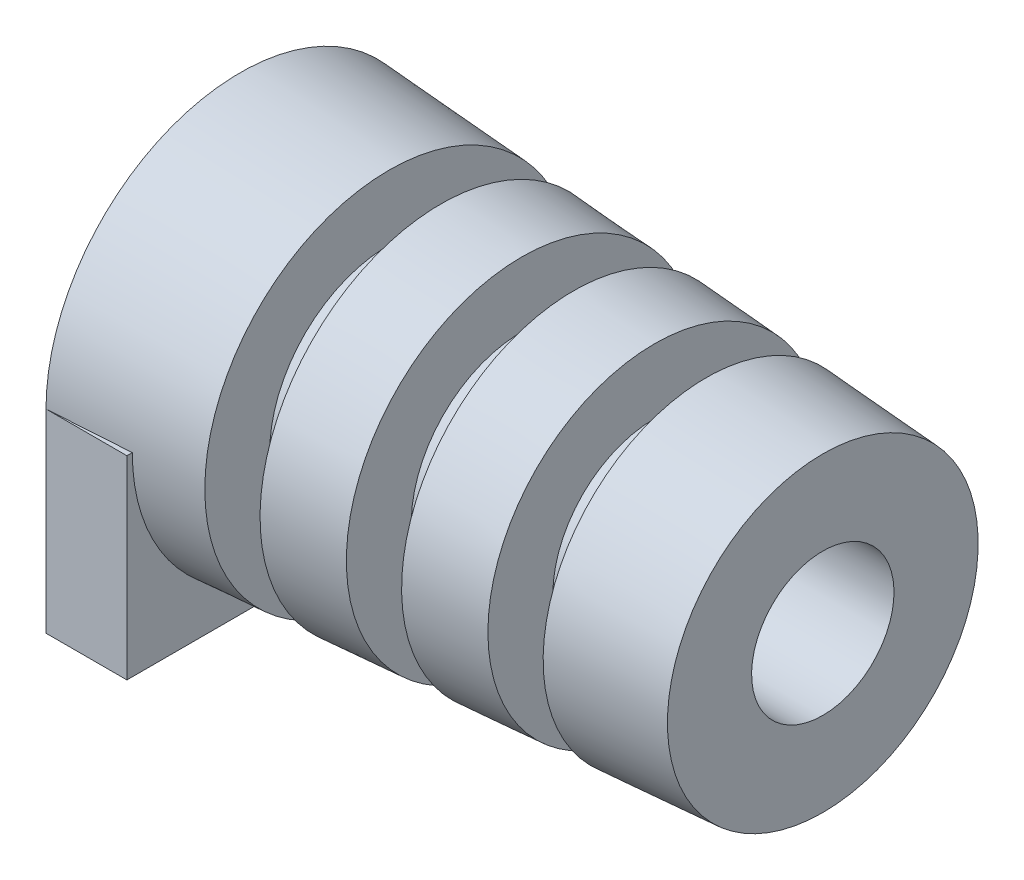
SolidWorks part; units mm, degrees
material "Rubber"
ref_plane "Front" through (0, 0, 0) normal (0, 0, 1) x (1, 0, 0)
ref_plane "Top" through (0, 0, 0) normal (0, 1, 0) x (1, 0, 0)
ref_plane "Right" through (0, 0, 0) normal (1, 0, 0) x (0, 0, -1)
sketch "Sketch2" plane through (54.9, 0, 50.4016) normal (0, 0, -1) x (-1, 0, 0)
  line L0 (54.6382, 2.5902) -> (31.7782, 2.5902)
  line L1 (36.3502, -1.0166) -> (36.3502, 1.5291)
  line L2 (36.3502, -2.2358) -> (36.3502, 2.5902) construction
  line L3 (54.6382, -2.2358) -> (54.6382, 2.5902)
  line L4 (54.6382, 5.3842) -> (31.7782, 5.3842) construction
  line L5 (31.7782, 2.5902) -> (31.7782, -0.7118)
  line L6 (31.7782, -0.7118) -> (36.3502, -1.0166)
  line L7 (48.7962, -1.8463) -> (48.7962, 0.6993)
  line L8 (46.7642, -1.7108) -> (46.7642, 0.8348)
  line L9 (43.5892, -1.4992) -> (43.5892, 1.0465)
  line L10 (41.5572, -1.3637) -> (41.5572, 1.1819)
  line L11 (38.3822, -1.152) -> (38.3822, 1.3936)
  line L12 (36.3502, 1.5291) -> (38.3822, 1.3936)
  line L13 (48.7962, -1.8463) -> (54.6382, -2.2358)
  line L14 (31.7782, -0.7118) -> (54.6382, -2.2358) construction
  line L15 (48.7962, -2.2358) -> (48.7962, 2.5902) construction
  line L16 (46.7642, -2.2358) -> (46.7642, 2.5902) construction
  line L17 (54.6382, 0.3099) -> (54.8072, 0.2986)
  line L18 (31.9472, 1.8226) -> (54.8072, 0.2986) construction
  line L19 (46.7642, 0.8348) -> (48.7962, 0.6993)
  line L20 (43.5892, -2.2358) -> (43.5892, 2.5902) construction
  line L21 (41.5572, -2.2358) -> (41.5572, 2.5902) construction
  line L22 (38.3822, -2.2358) -> (38.3822, 2.5902) construction
  line L23 (41.5572, 1.1819) -> (43.5892, 1.0465)
  line L24 (38.3822, -1.152) -> (41.5572, -1.3637)
  line L25 (43.5892, -1.4992) -> (46.7642, -1.7108)
  dimension "D1" = 7.62
  dimension "D2" = 22.86
  dimension "D3" = 6.096
  dimension "D4" = 2.794
  dimension "D5" = 5.842
  dimension "D6" = 2.032
  dimension "D7" = 3.175
  dimension "D8" = 2.032
  dimension "D9" = 3.175
  dimension "D10" = 2.54
  dimension "D11" = 2.032
revolve "Revolve-Thin2" add sketch "Sketch2" angle 360 about L4
sketch "Sketch4" plane through (0.2616, 0, 0) normal (-1, 0, 0) x (0, 0, 1)
  line L0 (42.7814, 5.3842) -> (58.0219, 5.3842) construction
  line L1 (42.7814, 5.3842) -> (42.7814, -2.236)
  line L2 (50.4016, -2.236) -> (50.4016, 13.0045) construction
  line L3 (42.7814, -2.236) -> (58.0219, -2.236)
  line L4 (57.5136, 5.3842) -> (58.0219, 5.3842)
  line L5 (43.2896, 5.3842) -> (42.7814, 5.3842)
  line L6 (58.0219, 5.3842) -> (58.0219, -2.236)
  circle A0 centre (50.4016, 5.3842) radius 7.6202 construction
  arc A1 (43.2896, 5.3842) -> (57.5136, 5.3842) centre (50.4016, 5.3842) ccw
  dimension "D1" = 7.6202
  dimension "D2" = 15.2404
extrude "Extrude2" add sketch "Sketch4" against normal blind 3.175
